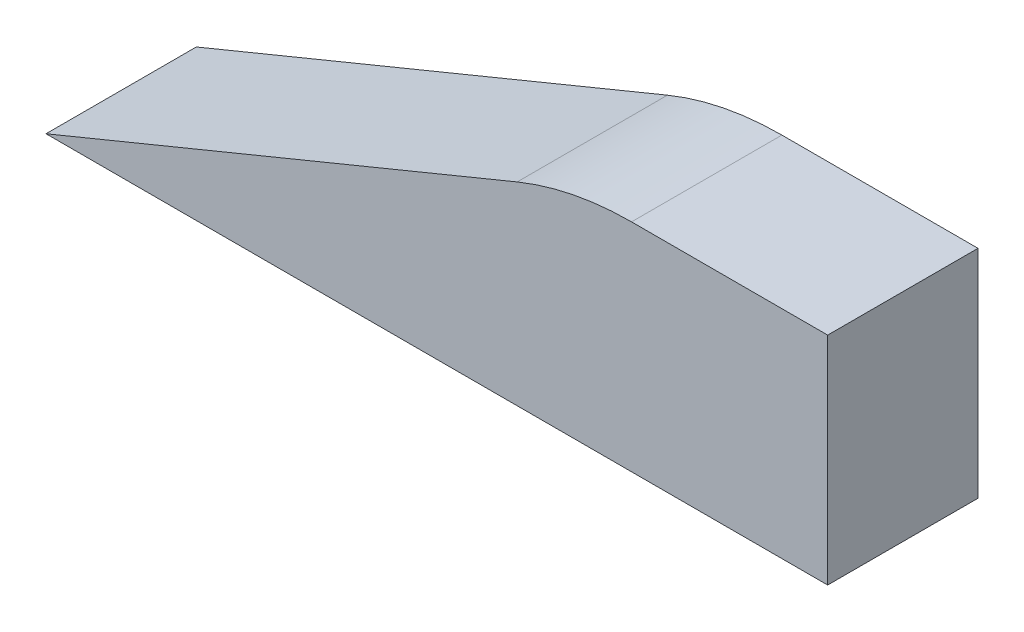
SolidWorks part; units mm, degrees
ref_plane "前视基准面" through (0, 0, 0) normal (0, 0, 1) x (1, 0, 0)
ref_plane "上视基准面" through (0, 0, 0) normal (0, 1, 0) x (1, 0, 0)
ref_plane "右视基准面" through (0, 0, 0) normal (1, 0, 0) x (0, 0, -1)
sketch "草图1" plane through (0, 0, 0) normal (0, 0, 1) x (1, 0, 0)
  line L0 (0, 0) -> (-35, 0)
  line L1 (0, 0) -> (0, 14.4)
  line L2 (-35, 0) -> (0, 14.4)
  dimension "D1" = 14.4
  dimension "D2" = 35
extrude "凸台-拉伸1" add sketch "草图1" along normal blind 10
sketch "草图3" plane through (0, 0, 0) normal (1, 0, 0) x (0, 0, -1)
  line L1 (-10, 14.4) -> (0, 14.4)
  line L2 (-10, 14.4) -> (-10, 0)
  line L3 (-10, 0) -> (0, 0)
  line L4 (0, 14.4) -> (0, 0)
extrude "凸台-拉伸2" add sketch "草图3" along normal blind 17
fillet "圆角1" radius 20 1 edges at (0, 14.4, 5)
